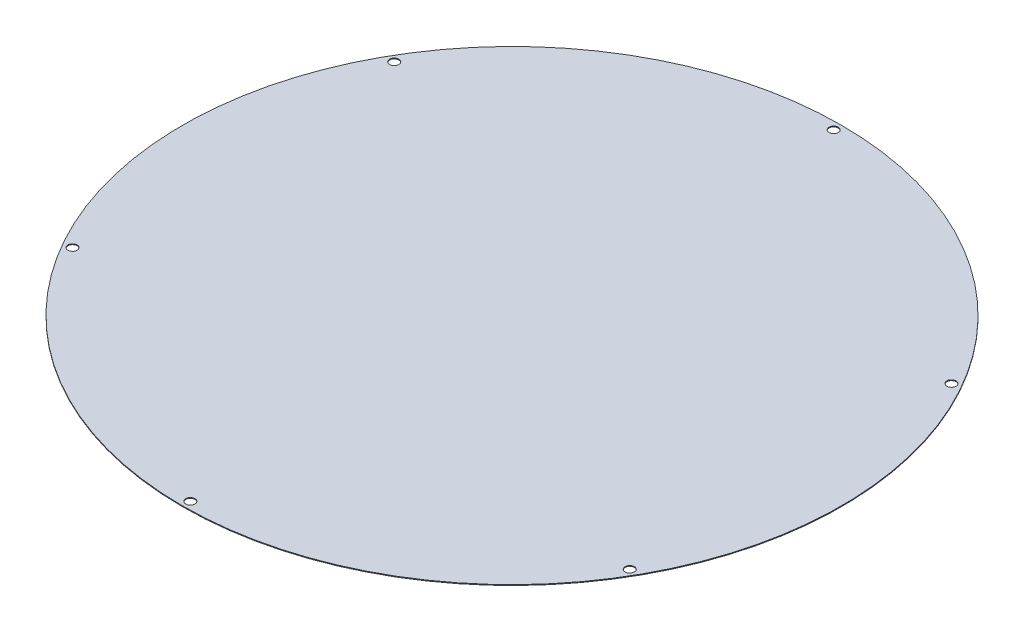
SolidWorks part; units mm, degrees
material "Copper"
ref_plane "Front Plane" through (0, 0, 0) normal (0, 0, 1) x (1, 0, 0)
ref_plane "Top Plane" through (0, 0, 0) normal (0, 1, 0) x (1, 0, 0)
ref_plane "Right Plane" through (0, 0, 0) normal (1, 0, 0) x (0, 0, -1)
sketch "Sketch1" plane through (0, 0, 0) normal (0, 1, 0) x (1, 0, 0)
  circle A0 centre (0, 0) radius 105
  circle A1 centre (0, 0) radius 100
  circle A2 centre (0, 0) radius 102.5 construction
  circle A3 centre (0, -102.5) radius 1.4732
  circle A4 centre (-88.7671, -51.2491) radius 1.4732
  circle A5 centre (-88.7661, 51.2509) radius 1.4732
  circle A6 centre (0.002, 102.5) radius 1.4732
  circle A7 centre (88.7691, 51.2491) radius 1.4732
  circle A8 centre (88.7681, -51.2509) radius 1.4732
  dimension "D1" = 210
  dimension "D3" = 205
  dimension "D4" = 2.9464
  dimension "D2" = 5
  dimension "D5" = 6
extrude "Boss-Extrude1" add sketch "Sketch1" along normal blind 0.254 contours A1 | A0 A8 A7 A6 A5 A4 A3 A1
